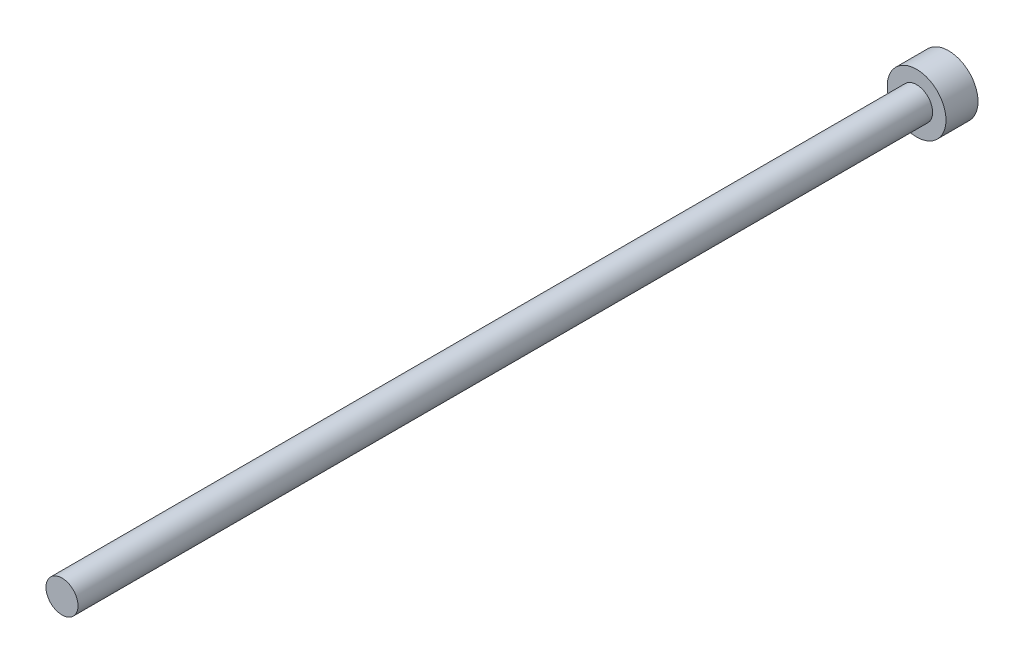
SolidWorks part; units mm, degrees
ref_plane "前视基准面" through (0, 0, 0) normal (0, 0, 1) x (1, 0, 0)
ref_plane "上视基准面" through (0, 0, 0) normal (0, 1, 0) x (1, 0, 0)
ref_plane "右视基准面" through (0, 0, 0) normal (1, 0, 0) x (0, 0, -1)
other "Configuration Table"
sketch "草图1" plane through (0, 0, 0) normal (0, 0, 1) x (1, 0, 0)
  circle A0 centre (0, 0) radius 2.75
extrude "凸台-拉伸1" add sketch "草图1" along normal mid plane 3
sketch "草图2" plane through (0, 0, 1.5) normal (0, 0, 1) x (1, 0, 0)
  circle A0 centre (0, 0) radius 1.5
extrude "凸台-拉伸2" add sketch "草图2" along normal blind 80
